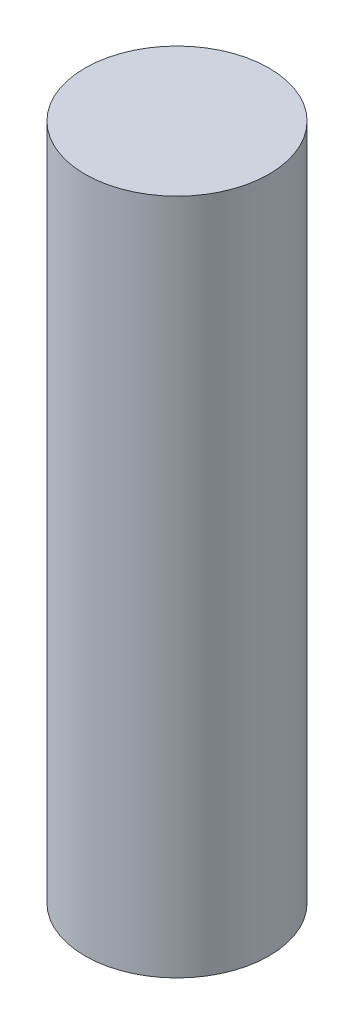
SolidWorks part; units mm, degrees
ref_plane "Front Plane" through (0, 0, 0) normal (0, 0, 1) x (1, 0, 0)
ref_plane "Top Plane" through (0, 0, 0) normal (0, 1, 0) x (1, 0, 0)
ref_plane "Right Plane" through (0, 0, 0) normal (1, 0, 0) x (0, 0, -1)
sketch "Sketch1" plane through (0, 0, 0) normal (0, 1, 0) x (1, 0, 0)
  circle A0 centre (0, 0) radius 2.5
  dimension "D1" = 5
extrude "Boss-Extrude1" add sketch "Sketch1" along normal blind 18.4
